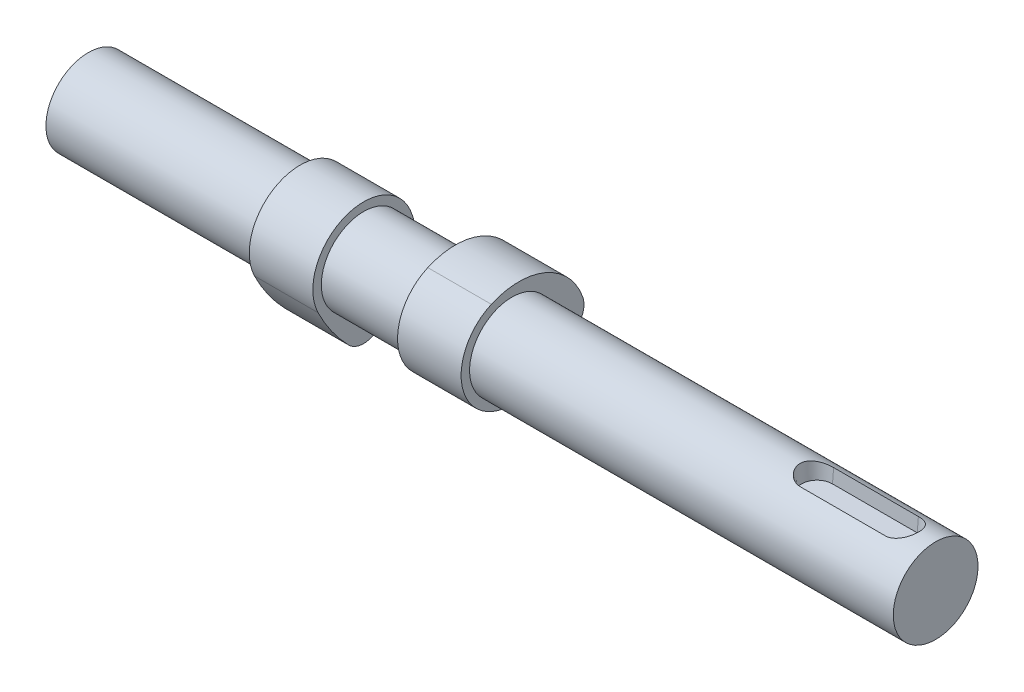
SolidWorks part; units mm, degrees
ref_plane "Front Plane" through (0, 0, 0) normal (0, 0, 1) x (1, 0, 0)
ref_plane "Top Plane" through (0, 0, 0) normal (0, 1, 0) x (1, 0, 0)
ref_plane "Right Plane" through (0, 0, 0) normal (1, 0, 0) x (0, 0, -1)
sketch "Sketch1" plane through (0, 0, 0) normal (1, 0, 0) x (0, 0, -1)
  circle A0 centre (0, 0) radius 10
  dimension "D1" = 20
extrude "Boss-Extrude1" add sketch "Sketch1" along normal blind 125 and the other way blind 75
sketch "Sketch2" plane through (0, 0, 0) normal (1, 0, 0) x (0, 0, -1)
  arc A0 (-4.8671, 10.9687) -> (5.3062, -10.7631) centre (0, 0) ccw
  arc A1 (-4.8671, 10.9687) -> (16.7127, 1.6619) centre (1.6224, -3.6562) cw
  arc A2 (5.3062, -10.7631) -> (15.4795, -3.5877) centre (-12.3812, 25.1139) ccw
  arc A3 (16.7127, 1.6619) -> (15.4795, -3.5877) centre (11.997, 0) cw
  dimension "D1" = 11
  dimension "D2" = 24
  dimension "D3" = 40
  dimension "D4" = 5
  dimension "D5" = 16
  dimension "D6" = 12.5
extrude "Boss-Extrude2" add sketch "Sketch2" along normal blind 15 from offset 10 separate body
mirror "Mirror1" about plane through (0, 0, 0) normal (1, 0, 0) of bodies 102
move or copy body "Body-Move/Copy1" bodies to move or copy 103 copy no rotation origin (0, 0, 0) rotation axis (-1, 0, 0) rotation angle 90 parameters "Angle Around Edge"=270
sketch "Sketch3" plane through (0, 0, 0) normal (0, 1, 0) x (1, 0, 0)
  line L0 (125, 10) -> (125, -10) construction
  line L1 (125, -10) -> (125, 10) construction
  line L2 (125, 10) -> (-75, 10) construction
  line L3 (125, 0) -> (80.0337, 0) construction
  line L4 (-75, 0) -> (125, 0) construction
  line L5 (97, 0) -> (117, 0) construction
  line L6 (97, 4) -> (117, 4)
  line L7 (97, -4) -> (117, -4)
  arc A0 (97, 4) -> (97, -4) centre (97, 0) ccw
  arc A1 (117, -4) -> (117, 4) centre (117, 0) ccw
  point P13 (107, 0)
  dimension "D2" = 4
  dimension "D1" = 20
  dimension "D3" = 16
extrude "Cut-Extrude1" cut sketch "Sketch3" against normal blind 4 draft 5 from offset 10
